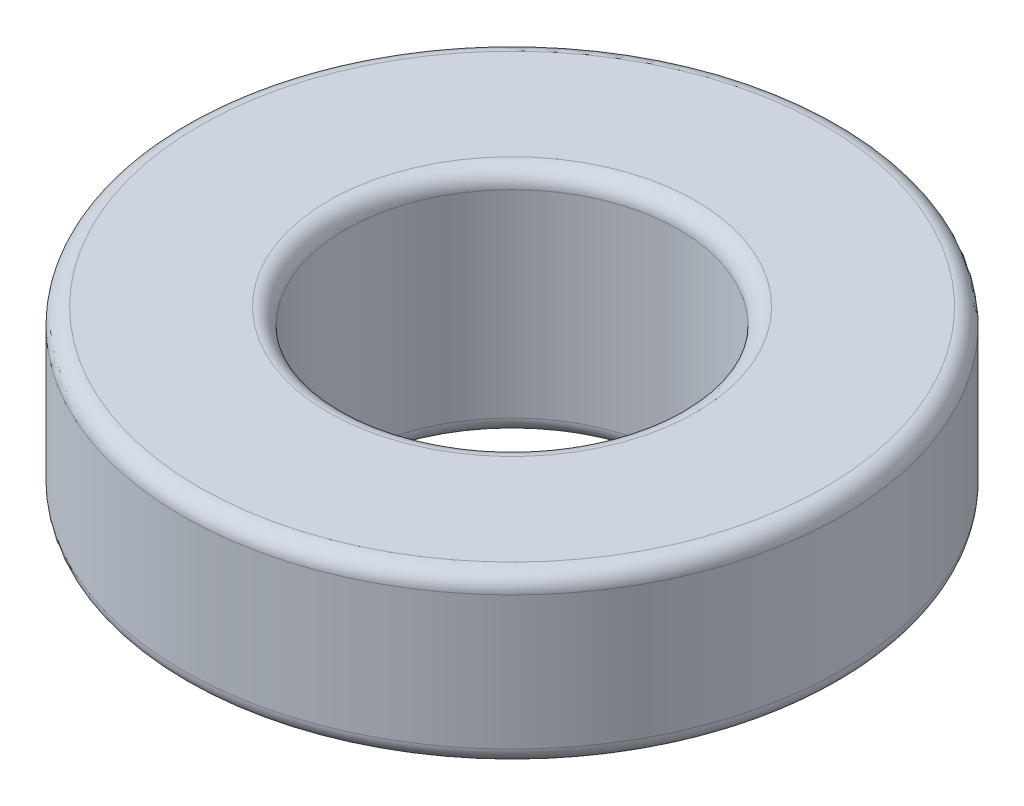
SolidWorks part; units mm, degrees
material "铸造碳钢"
ref_plane "前视基准面" through (0, 0, 0) normal (0, 0, 1) x (1, 0, 0)
ref_plane "上视基准面" through (0, 0, 0) normal (0, 1, 0) x (1, 0, 0)
ref_plane "右视基准面" through (0, 0, 0) normal (1, 0, 0) x (0, 0, -1)
sketch "草图1" plane through (0, 0, 0) normal (0, 1, 0) x (1, 0, 0)
  circle A0 centre (0, 0) radius 2
  circle A1 centre (0, 0) radius 2.69
  dimension "孔径" = 4
  dimension "外径" = 5.38
extrude "凸台-拉伸1" add sketch "草图1" along normal blind 0.77
sketch "草图2" plane through (0, 0.77, 0) normal (0, 1, 0) x (1, 0, 0)
  circle A0 centre (0, 0) radius 2
  circle A1 centre (0, 0) radius 3.95
  circle A2 centre (0, 0) radius 2 construction
  dimension "翻边外径" = 7.9
extrude "凸台-拉伸2" add sketch "草图2" along normal blind 2
fillet "圆角1" radius 0.2 4 edges at (0, 0, 2) (0, 2.77, 2) (0, 2.77, 3.95) (0, 0.77, 3.95)
other "冻结***"
